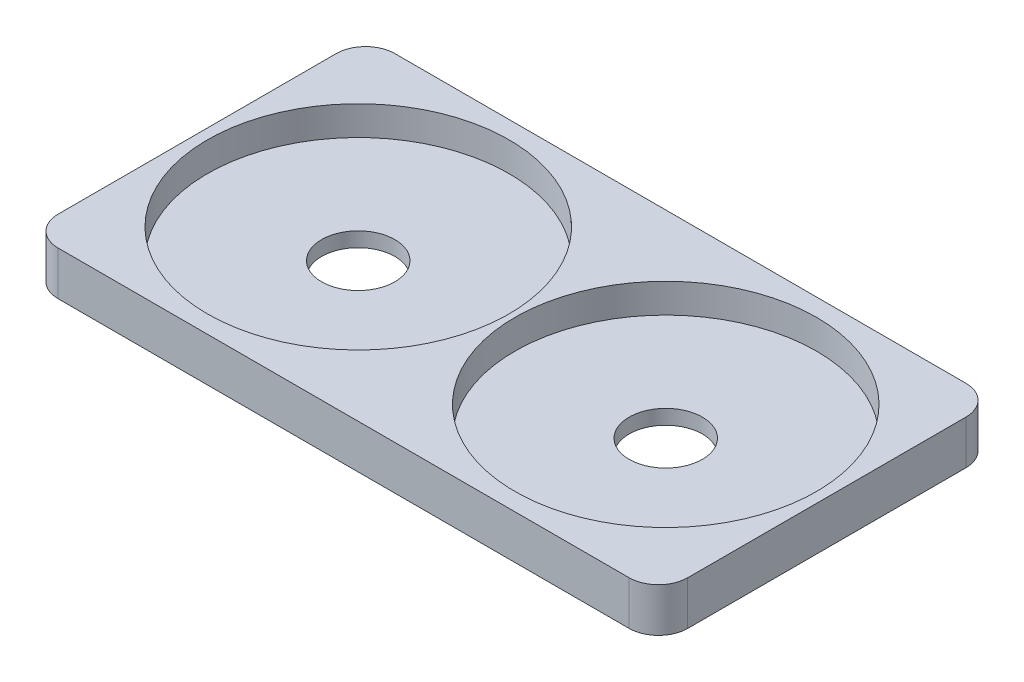
SolidWorks part; units mm, degrees
ref_plane "Front" through (0, 0, 0) normal (0, 0, 1) x (1, 0, 0)
ref_plane "Top" through (0, 0, 0) normal (0, 1, 0) x (1, 0, 0)
ref_plane "Right" through (0, 0, 0) normal (1, 0, 0) x (0, 0, -1)
sketch "Croquis1" plane through (0, 0, 0) normal (0, 1, 0) x (1, 0, 0)
  line L1 (-21.5, -11.5) -> (21.5, -11.5)
  line L2 (-21.5, -11.5) -> (-21.5, 11.5)
  line L3 (-21.5, 11.5) -> (21.5, 11.5)
  line L4 (21.5, -11.5) -> (21.5, 11.5)
  line L5 (-21.5, -11.5) -> (21.5, 11.5) construction
  line L6 (-21.5, 11.5) -> (21.5, -11.5) construction
  point P0 (0, 0)
  dimension "D1" = 43
  dimension "D2" = 23
extrude "Saliente-Extruir1" add sketch "Croquis1" along normal blind 3
fillet "Redondeo1" radius 2 4 edges at (-21.5, 1.5, -11.5) (21.5, 1.5, -11.5) (21.5, 1.5, 11.5) (-21.5, 1.5, 11.5)
sketch "Croquis2" plane through (0, 3, 0) normal (0, 1, 0) x (1, 0, 0)
  line L0 (-1000, 0) -> (49000, 0) construction
  line L1 (0, -1000) -> (0, 49000) construction
  line L2 (10.5, -1000) -> (10.5, 49000) construction
  line L3 (-10.5, -1000) -> (-10.5, 49000) construction
  circle A0 centre (-10.5, 0) radius 10.3
  circle A1 centre (10.5, 0) radius 10.3
  dimension "D3" = 20.6
  dimension "D1" = 10.5
  dimension "D2" = 10.5
extrude "Cortar-Extruir1" cut sketch "Croquis2" against normal blind 2
sketch "Croquis3" plane through (0, 1, 0) normal (0, 1, 0) x (1, 0, 0)
  circle A0 centre (-10.5, 0) radius 2.5
  circle A1 centre (10.5, 0) radius 2.5
  dimension "D1" = 5
  dimension "D2" = 5
extrude "Cortar-Extruir2" cut sketch "Croquis3" against normal up to surface (1 mm away) up to face at (0, 0, 0)
